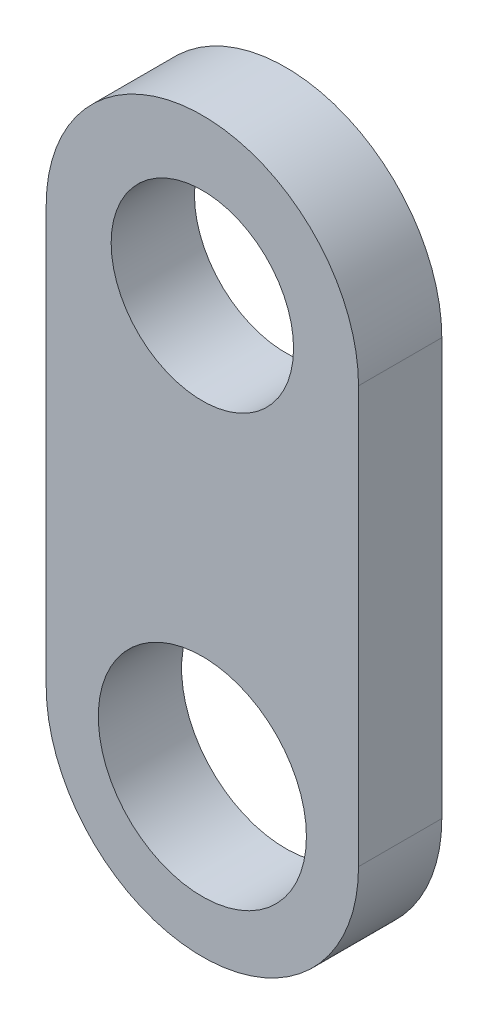
SolidWorks part; units mm, degrees
material "6061-T6 (SS)"
ref_plane "Front Plane" through (0, 0, 0) normal (0, 0, 1) x (1, 0, 0)
ref_plane "Top Plane" through (0, 0, 0) normal (0, 1, 0) x (1, 0, 0)
ref_plane "Right Plane" through (0, 0, 0) normal (1, 0, 0) x (0, 0, -1)
sketch "Sketch2" plane through (0, 0, 0) normal (0, 0, 1) x (1, 0, 0)
  line L0 (0, 0) -> (0, 50.8) construction
  line L1 (-19.05, 0) -> (-19.05, 50.8)
  line L2 (19.05, 0) -> (19.05, 50.8)
  arc A0 (-19.05, 0) -> (19.05, 0) centre (0, 0) ccw
  arc A1 (19.05, 50.8) -> (-19.05, 50.8) centre (0, 50.8) ccw
  circle A2 centre (0, 50.8) radius 11.1252
  circle A3 centre (0, 0) radius 12.6937
  point P3 (0, 25.4)
  dimension "D3" = 22.2504
  dimension "D4" = 25.3873
  dimension "D1" = 38.1
  dimension "D2" = 50.8
extrude "Boss-Extrude1" add sketch "Sketch2" along normal mid plane 10.16
equation "\"Link Width\"= 1.5in"
equation "\"Hole Spacing\"= 2in"
equation "\"Link Thickness\"= 0.4in"
equation "\"Bracket Bar Diameter\"= \"Bar Diameter\""
equation "\"Second Shaft Diameter\"= 1in"
equation "\"D1@Sketch2\"=\"Link Width\""
equation "\"D2@Sketch2\"=\"Hole Spacing\""
equation "\"D1@Boss-Extrude1\"=\"Link Thickness\""
equation "\"D3@Sketch2\" = \"Bracket Hole Diameter\""
equation "\"D4@Sketch2\" = \"Shaft Hole Diameter\""
equation "\"Bar Diameter\" = \"Minimum Bar Diameter\"+\"Diameter Allowance\""
equation "\"Bracket Hole Diameter\"= \"Bracket Bar Diameter\" + 0.001in"
equation "\"Shaft Hole Diameter\"= \"Second Shaft Diameter\" - 0.0005in"
